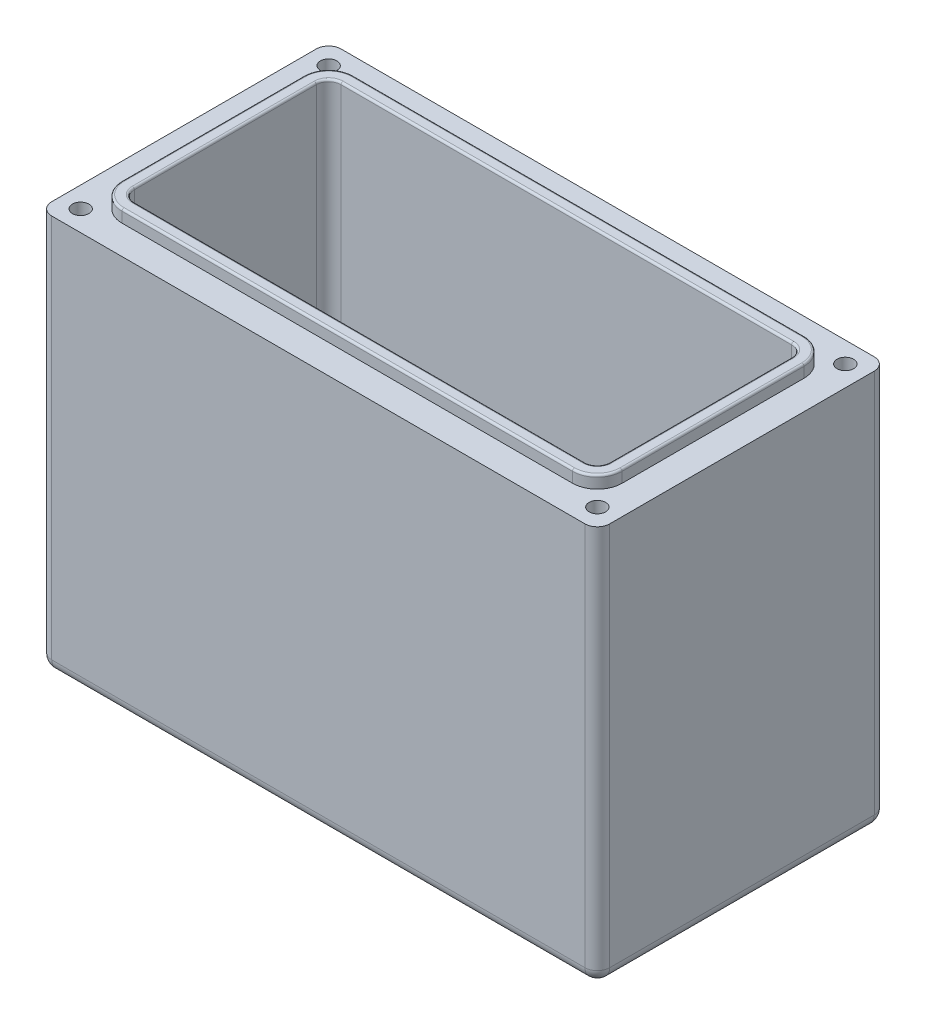
SolidWorks part; units mm, degrees
ref_plane "Front Plane" through (0, 0, 0) normal (0, 0, 1) x (1, 0, 0)
ref_plane "Top Plane" through (0, 0, 0) normal (0, 1, 0) x (1, 0, 0)
ref_plane "Right Plane" through (0, 0, 0) normal (1, 0, 0) x (0, 0, -1)
sketch "Sketch1" plane through (0, 0, 0) normal (0, 1, 0) x (1, 0, 0)
  line L1 (0, 0) -> (135, 0)
  line L2 (0, 0) -> (0, -70)
  line L3 (0, -70) -> (135, -70)
  line L4 (135, 0) -> (135, -70)
  dimension "D1" = 135
  dimension "D2" = 70
extrude "Boss-Extrude1" add sketch "Sketch1" along normal blind 96
sketch "Sketch10" plane through (0, 96, 0) normal (0, 1, 0) x (1, 0, 0)
  line L8 (10, -10) -> (10, -60)
  line L9 (10, -60) -> (125, -60)
  line L10 (125, -60) -> (125, -10)
  line L11 (125, -10) -> (10, -10)
  line L12 (10, -10) -> (10, -60)
  line L13 (10, -60) -> (125, -60)
  line L14 (125, -60) -> (125, -10)
  line L15 (125, -10) -> (10, -10)
  dimension "D1" = 10
extrude "Cut-Extrude7" cut sketch "Sketch10" against normal blind 91
sketch "Sketch2" plane through (0, 5, 0) normal (0, 1, 0) x (1, 0, 0)
  line L0 (98.96, -21) -> (98.96, -49) construction
  line L1 (125, -60) -> (125, -10) construction
  line L2 (125, -60) -> (125, -10) construction
  circle A0 centre (58.96, -21) radius 2.25
  circle A1 centre (98.96, -21) radius 2.25
  circle A2 centre (58.96, -49) radius 2.25
  circle A3 centre (98.96, -49) radius 2.25
  point P12 (125, -35)
  point P13 (98.96, -35)
  dimension "D1" = 4.5
  dimension "D4" = 26.04
  dimension "D2" = 28
  dimension "D3" = 40
extrude "Cut-Extrude1" cut sketch "Sketch2" against normal through all
sketch "Sketch3" plane through (0, 5, 0) normal (0, 1, 0) x (1, 0, 0)
  line L0 (98.96, -21) -> (98.96, -49) construction
  circle A0 centre (87.5, -35) radius 5
  point P6 (98.96, -35)
  dimension "D1" = 10
  dimension "D2" = 11.46
extrude "Cut-Extrude2" cut sketch "Sketch3" against normal through all
sketch "Sketch6" plane through (0, 96, 0) normal (0, 1, 0) x (1, 0, 0)
  line L0 (135, -70) -> (135, 0) construction
  line L1 (0, -70) -> (135, -70) construction
  line L2 (135, 0) -> (0, 0) construction
  line L3 (0, 0) -> (0, -70) construction
  line L4 (130, -65) -> (5, -65) construction
  circle A0 centre (130, -65) radius 2
  circle A1 centre (5, -65) radius 2
  circle A4 centre (5, -5) radius 2
  circle A6 centre (130, -5) radius 2
  dimension "D3" = 4
  dimension "D1" = 5
  dimension "D2" = 5
  dimension "D4" = 5
  dimension "D5" = 5
extrude "Cut-Extrude5" cut sketch "Sketch6" against normal blind 7.4
sketch "Sketch7" plane through (0, 5, 0) normal (0, 1, 0) x (1, 0, 0)
  circle A1 centre (87.5, -35) radius 5 construction
  circle A3 centre (87.5, -35) radius 8.25
  circle A6 centre (87.5, -35) radius 5
  dimension "D1" = 16.5
sketch "Sketch8" plane through (0, 0, 0) normal (0, -1, 0) x (1, 0, 0)
  circle A16 centre (87.5, 35) radius 12.5
  dimension "D1" = 25
extrude "Cut-Extrude6" [suppressed] cut sketch "Sketch8" against normal blind 5.5
sketch "Sketch17" plane through (0, 0, 85) normal (1, 0, 0) x (0, 0, -1)
  line L2 (15, 96) -> (85, 96) construction
  circle A0 centre (50, 56) radius 8
  point P4 (50, 96)
  dimension "D1" = 16
  dimension "D2" = 40
extrude "Cut-Extrude9" cut sketch "Sketch17" along normal up to next
sketch "Sketch15" [suppressed] plane through (0, 79, 0) normal (0, -1, 0) x (1, 0, 0)
  circle A0 centre (6, 69) radius 3.5
  circle A1 centre (75, 69) radius 3.5
  circle A2 centre (144, 69) radius 3.5
  circle A3 centre (144, 37.5) radius 3.5
  circle A4 centre (144, 6) radius 3.5
  circle A5 centre (75, 6) radius 3.5
  circle A6 centre (6, 6) radius 3.5
  circle A7 centre (6, 37.5) radius 3.5
  circle A8 centre (6, 69) radius 1.5 construction
  circle A9 centre (144, 69) radius 1.5 construction
  dimension "D1" = 7
extrude "Cut-Extrude8" [suppressed] cut sketch "Sketch15" along normal blind 10
sketch "Sketch19" plane through (0, 88.6, 0) normal (0, 1, 0) x (1, 0, 0)
  circle A0 centre (5, -5) radius 1
  circle A2 centre (130, -5) radius 1
  circle A4 centre (130, -65) radius 1
  circle A6 centre (5, -65) radius 1
extrude "Cut-Extrude12" cut sketch "Sketch19" against normal blind 20
sketch "Sketch20" [suppressed] plane through (0, 0, 12) normal (0, 0, 1) x (1, 0, 0)
  line L0 (0, 96) -> (0, 2) construction
  line L1 (34.5, 48.5) -> (75.5, 48.5)
  line L2 (34.5, 48.5) -> (34.5, 75.5)
  line L3 (34.5, 75.5) -> (75.5, 75.5)
  line L4 (75.5, 48.5) -> (75.5, 75.5)
  line L5 (34.5, 48.5) -> (75.5, 75.5) construction
  line L6 (34.5, 75.5) -> (75.5, 48.5) construction
  line L7 (134, 96) -> (5, 96) construction
  point P0 (55, 62)
  dimension "D1" = 41
  dimension "D2" = 27
  dimension "D3" = 55
  dimension "D4" = 34
sketch "Sketch23" plane through (10, 0, 0) normal (1, 0, 0) x (0, 0, -1)
  circle A1 centre (-35, 56) radius 8 construction
  circle A3 centre (-35, 56) radius 12
  dimension "D1" = 24
extrude "Cut-Extrude13" cut sketch "Sketch23" against normal blind 7
hole_wizard "CSK for ST2.2 Cross recessed CTSK head tapping screws1" [suppressed] positions "Sketch21" profile "Sketch22" countersink size "ST2.2" standard "GB"
sketch "Sketch21" [suppressed] plane through (0, 0, 0) normal (0, 0, 1) x (1, 0, 0)
  point P0 (34.5, 75.5)
  point P3 (34.5, 48.5)
  point P6 (75.5, 48.5)
  point P9 (75.5, 75.5)
sketch "Sketch22" plane through (34.5, 75.5, 0) normal (1, 0, 0) x (0, 1, 0)
  line L0 (0, 0) -> (0, 12)
  line L1 (0, 12) -> (1.2, 12)
  line L2 (1.2, 12) -> (1.2, 1)
  line L3 (1.2, 1) -> (2.2, 0)
  line L5 (2.2, 0) -> (0, 0)
  line L6 (-1.2, 1) -> (-2.2, 0) construction
  line L11 (0, -6.35) -> (0, 107.95) construction
  dimension "Thru Hole Dia." = 2.4
  dimension "Thru Hole Depth" = 12
  dimension "Near C'Sink Dia." = 4.4
  dimension "Near C'Sink Angle" = 90
extrude "Cut-Extrude14" cut sketch "Sketch7" against normal blind 4.5
sketch "Sketch24" plane through (0, 5, 0) normal (0, 1, 0) x (1, 0, 0)
  circle A18 centre (58.96, -21) radius 3.25
  circle A19 centre (98.96, -21) radius 3.25
  circle A20 centre (58.96, -49) radius 3.25
  circle A21 centre (98.96, -49) radius 3.25
  dimension "D1" = 6.5
extrude "Cut-Extrude15" cut sketch "Sketch24" against normal blind 2
fillet "Fillet1" radius 3 16 edges at (125, 5, 35) (67.5, 0, 0) (67.5, 0, 70) (0, 0, 35) (10, 50.5, 60) (135, 48, 70) (0, 48, 0) (135, 48, 0) (135, 0, 35) (0, 48, 70) (125, 50.5, 60) (67.5, 5, 60) (10, 5, 35) (10, 50.5, 10) (125, 50.5, 10) (67.5, 5, 10)
sketch "Sketch25" plane through (0, 96, 0) normal (0, 1, 0) x (1, 0, 0)
  line L37 (125, -13) -> (125, -57) construction
  line L38 (122, -60) -> (13, -60) construction
  line L39 (13, -10) -> (122, -10) construction
  line L40 (10, -57) -> (10, -13) construction
  line L41 (128, -57) -> (128, -13)
  line L42 (122, -7) -> (13, -7)
  line L43 (13, -63) -> (122, -63)
  line L44 (7, -13) -> (7, -57)
  line L45 (128, -57) -> (128, -13)
  line L46 (122, -7) -> (13, -7)
  line L47 (13, -63) -> (122, -63)
  line L48 (7, -13) -> (7, -57)
  line L49 (125, -13) -> (125, -57)
  line L50 (122, -60) -> (13, -60)
  line L51 (13, -10) -> (122, -10)
  line L52 (10, -57) -> (10, -13)
  arc A29 (125, -13) -> (122, -10) centre (122, -13) ccw construction
  arc A30 (122, -60) -> (125, -57) centre (122, -57) ccw construction
  arc A31 (10, -57) -> (13, -60) centre (13, -57) ccw construction
  arc A32 (13, -10) -> (10, -13) centre (13, -13) ccw construction
  arc A33 (122, -63) -> (128, -57) centre (122, -57) ccw
  arc A34 (128, -13) -> (122, -7) centre (122, -13) ccw
  arc A35 (7, -57) -> (13, -63) centre (13, -57) ccw
  arc A36 (13, -7) -> (7, -13) centre (13, -13) ccw
  arc A37 (122, -63) -> (128, -57) centre (122, -57) ccw
  arc A38 (128, -13) -> (122, -7) centre (122, -13) ccw
  arc A39 (7, -57) -> (13, -63) centre (13, -57) ccw
  arc A40 (13, -7) -> (7, -13) centre (13, -13) ccw
  arc A41 (125, -13) -> (122, -10) centre (122, -13) ccw
  arc A42 (122, -60) -> (125, -57) centre (122, -57) ccw
  arc A43 (10, -57) -> (13, -60) centre (13, -57) ccw
  arc A44 (13, -10) -> (10, -13) centre (13, -13) ccw
  dimension "D1" = 3
extrude "Boss-Extrude2" add sketch "Sketch25" along normal blind 3
fillet "Fillet2" radius 0.5 16 edges at (10.8787, 99, 10.8787) (10, 99, 35) (10.8787, 99, 59.1213) (67.5, 99, 60) (124.1213, 99, 59.1213) (125, 99, 35) (124.1213, 99, 10.8787) (67.5, 99, 10) (67.5, 99, 63) (8.7574, 99, 61.2426) (7, 99, 35) (8.7574, 99, 8.7574) (67.5, 99, 7) (126.2426, 99, 8.7574) (128, 99, 35) (126.2426, 99, 61.2426)
